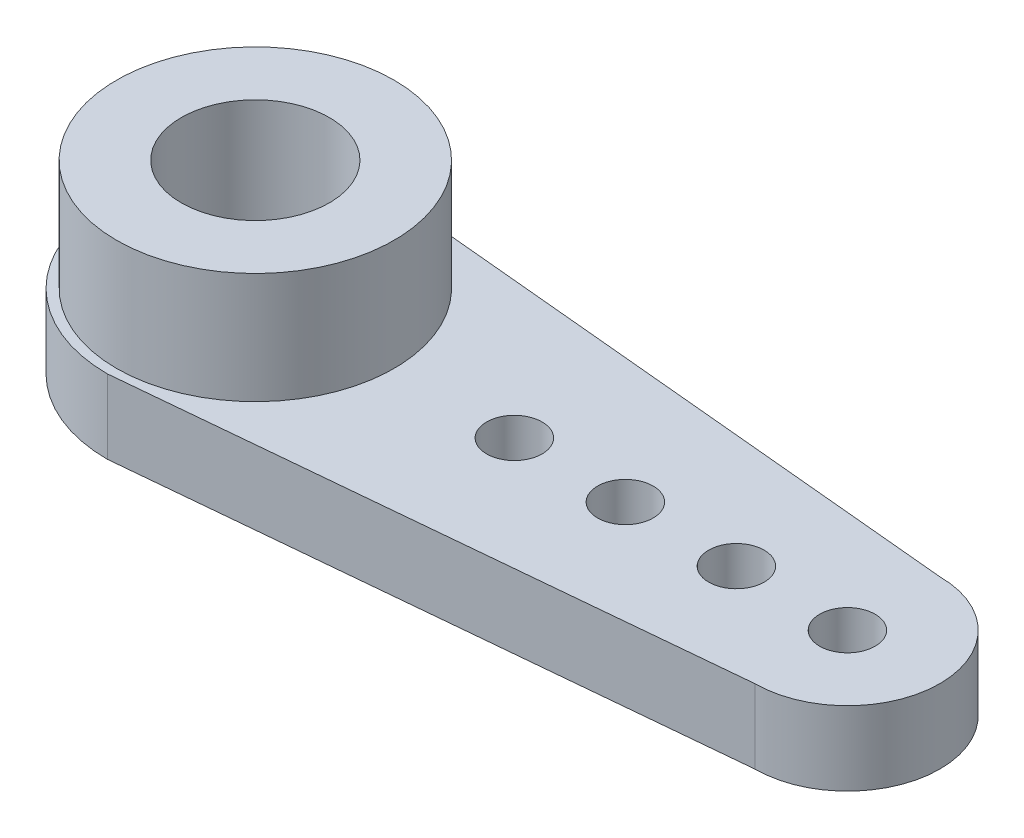
SolidWorks part; units mm, degrees
ref_plane "Plan de face" through (0, 0, 0) normal (0, 0, 1) x (1, 0, 0)
ref_plane "Plan de dessus" through (0, 0, 0) normal (0, 1, 0) x (1, 0, 0)
ref_plane "Plan de droite" through (0, 0, 0) normal (1, 0, 0) x (0, 0, -1)
sketch "Esquisse1" plane through (0, 0, 0) normal (0, 1, 0) x (1, 0, 0)
  line L1 (0, 4) -> (16, 2.5)
  line L2 (0, -4) -> (16, -2.5)
  arc A0 (0, 4) -> (0, -4) centre (0, 0) ccw
  circle A2 centre (16, 0) radius 0.75
  circle A3 centre (13, 0) radius 0.75
  circle A4 centre (10, 0) radius 0.75
  circle A5 centre (7, 0) radius 0.75
  circle A6 centre (0, 0) radius 1
  arc A7 (16, -2.5) -> (16, 2.5) centre (16, 0) ccw
  dimension "D1" = 8
  dimension "D4" = 2
  dimension "D5" = 1.5
  dimension "D6" = 1.5
  dimension "D7" = 1.5
  dimension "D8" = 1.5
  dimension "D9" = 3
  dimension "D10" = 3
  dimension "D11" = 3
  dimension "D3" = 16
extrude "Boss.-Extru.1" add sketch "Esquisse1" along normal blind 2
sketch "Esquisse2" plane through (0, 2, 0) normal (0, 1, 0) x (1, 0, 0)
  circle A0 centre (0, 0) radius 3.75
  circle A1 centre (0, 0) radius 2
  dimension "D1" = 4
  dimension "D2" = 7.5
extrude "Boss.-Extru.2" add sketch "Esquisse2" along normal blind 3
